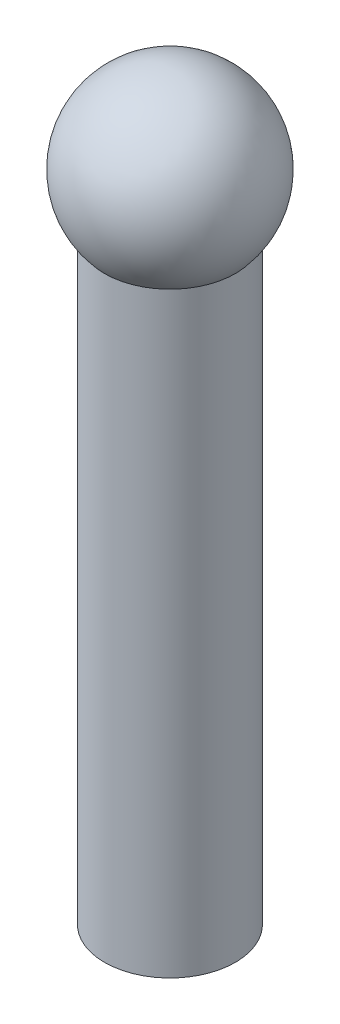
SolidWorks part; units mm, degrees
ref_plane "Front Plane" through (0, 0, 0) normal (0, 0, 1) x (1, 0, 0)
ref_plane "Top Plane" through (0, 0, 0) normal (0, 1, 0) x (1, 0, 0)
ref_plane "Right Plane" through (0, 0, 0) normal (1, 0, 0) x (0, 0, -1)
sketch "Sketch1" plane through (0, 0, 0) normal (0, 1, 0) x (1, 0, 0)
  circle A0 centre (0, 0) radius 7.5
  dimension "D1" = 15
extrude "Boss-Extrude1" add sketch "Sketch1" along normal blind 75
sketch "Sketch3" plane through (0, 75, 0) normal (0, 1, 0) x (1, 0, 0)
  line L0 (0, 10) -> (0, -10)
  arc A0 (0, 10) -> (0, -10) centre (0, 0) cw
  dimension "D1" = 10
  dimension "D2" = 10
revolve "Revolve1" add sketch "Sketch3" angle 360 about L0
